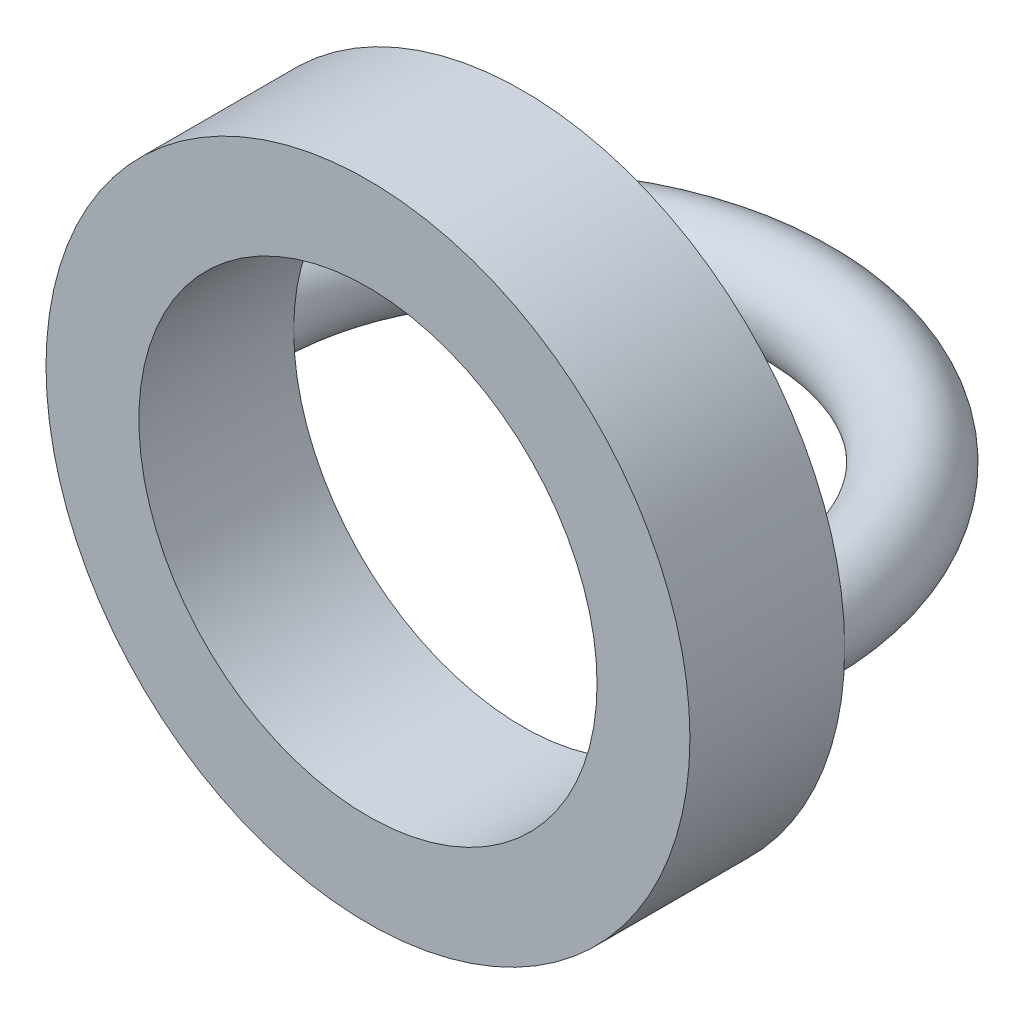
SolidWorks part; units mm, degrees
ref_plane "Front Plane" through (0, 0, 0) normal (0, 0, 1) x (1, 0, 0)
ref_plane "Top Plane" through (0, 0, 0) normal (0, 1, 0) x (1, 0, 0)
ref_plane "Right Plane" through (0, 0, 0) normal (1, 0, 0) x (0, 0, -1)
sketch "Sketch1" plane through (0, 0, 0) normal (0, 0, 1) x (1, 0, 0)
  circle A0 centre (0, 0) radius 7.4
  circle A1 centre (0, 0) radius 10.4
  dimension "D1" = 14.8
  dimension "D2" = 20.8
extrude "Boss-Extrude1" add sketch "Sketch1" along normal blind 5
sketch "Sketch5" plane through (0, 0, 0) normal (0, 0, -1) x (-1, 0, 0)
  circle A0 centre (8.9, 0) radius 1.5
  dimension "D2" = 3
  dimension "D1" = 8.9
sketch "Sketch6" plane through (0, 0, 0) normal (0, 1, 0) x (1, 0, 0)
  arc A0 (-8.9, 0) -> (8.9, 0) centre (0, 0) cw
sweep "Sweep1" add profiles "Sketch5" path "Sketch6"
